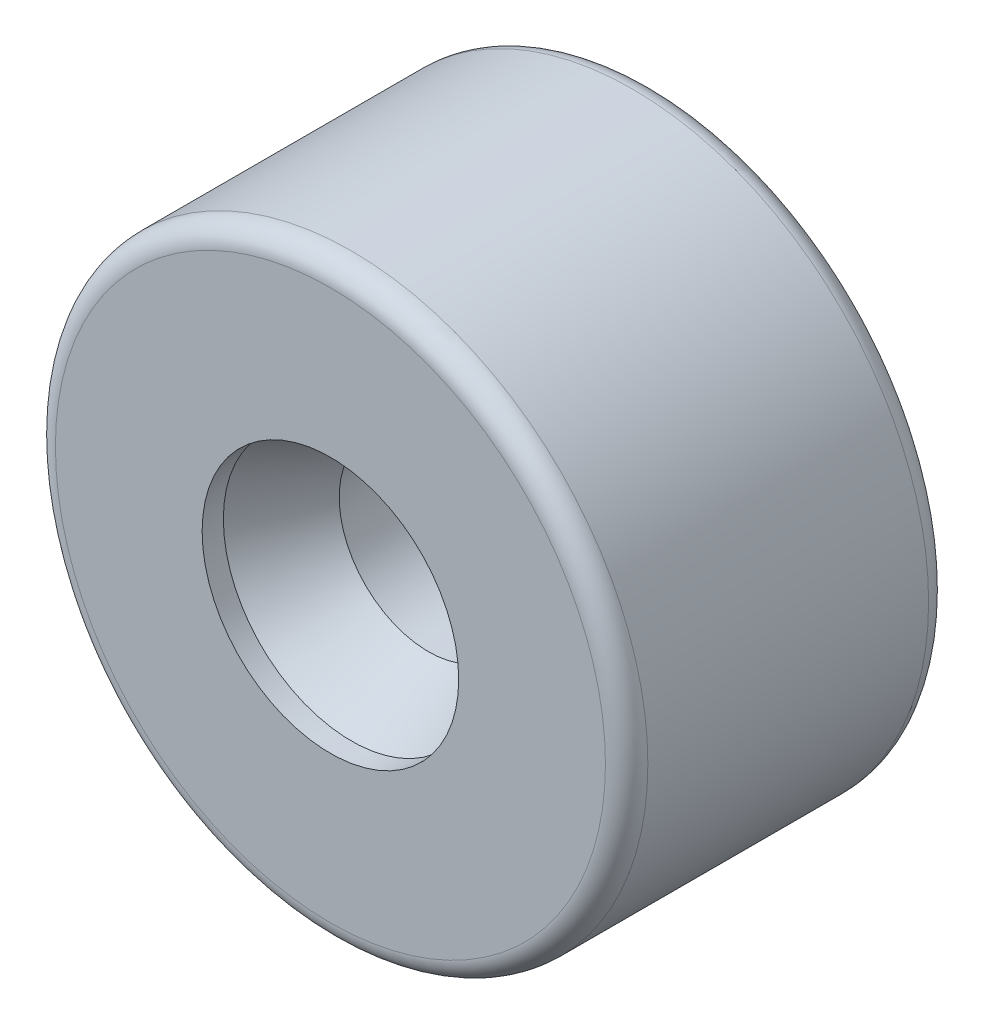
SolidWorks part; units mm, degrees
ref_plane "Front Plane" through (0, 0, 0) normal (0, 0, 1) x (1, 0, 0)
ref_plane "Top Plane" through (0, 0, 0) normal (0, 1, 0) x (1, 0, 0)
ref_plane "Right Plane" through (0, 0, 0) normal (1, 0, 0) x (0, 0, -1)
sketch "Sketch1" plane through (0, 0, 0) normal (1, 0, 0) x (0, 0, -1)
  line L0 (0, 10) -> (0, -10) construction
  line L1 (-361.4789, 0) -> (361.4789, 0) construction
  line L2 (30, 45.0552) -> (-30, 45.0552)
  line L3 (-30, 45.0552) -> (-66.2, 63.5)
  line L4 (-66.2, 63.5) -> (-76.2, 63.5)
  line L5 (-76.2, 63.5) -> (-76.2, 60.5)
  line L6 (-76.2, 60.5) -> (-66.2, 60.5)
  line L7 (-66.2, 60.5) -> (-30, 42.0552)
  line L8 (-30, 42.0552) -> (-1.5, 42.0552)
  line L9 (-1.5, 42.0552) -> (-1.5, 10)
  line L11 (-1.5, 10) -> (1.5, 10)
  line L12 (0, 10) -> (0, 78.3387) construction
  line L13 (1.5, 42.0552) -> (1.5, 10)
  line L14 (30, 42.0552) -> (1.5, 42.0552)
  line L15 (30, 45.0552) -> (66.2, 63.5)
  line L16 (66.2, 60.5) -> (30, 42.0552)
  line L17 (76.2, 60.5) -> (66.2, 60.5)
  line L18 (76.2, 63.5) -> (76.2, 60.5)
  line L19 (66.2, 63.5) -> (76.2, 63.5)
  point P4 (0, 0)
  point P8 (0, 0)
  point P23 (0, 45.0552)
  dimension "D1" = 153
  dimension "D2" = 30
  dimension "D3" = 10
  dimension "D4" = 76.2
  dimension "D5" = 3
  dimension "D6" = 63.5
  dimension "D7" = 1.5
  dimension "D8" = 3
  dimension "D9" = 10
revolve "Revolve1" add sketch "Sketch1" angle 360 about L1
sketch "Sketch2" plane through (0, 0, -1.5) normal (0, 0, -1) x (-1, 0, 0)
  circle A0 centre (0, 0) radius 30
  circle A1 centre (0, 30) radius 4
  circle A2 centre (30, 0) radius 4
  circle A3 centre (0, -30) radius 4
  circle A4 centre (-30, 0) radius 4
  dimension "D1" = 60
  dimension "D2" = 8
extrude "Cut-Extrude1" cut sketch "Sketch2" against normal blind 10 contours A0 A1 | A0 A1 | A0 A4 | A0 A4 | A0 A2 | A0 A2 | A0 A3 | A0 A3
sketch "Sketch3" plane through (0, 0, 0) normal (1, 0, 0) x (0, 0, -1)
  line L0 (0, 73.5893) -> (0, -73.5893) construction
  line L1 (-155.8032, 0) -> (155.8032, 0) construction
  line L2 (-66.2, 139.7) -> (66.2, 139.7)
  line L3 (-76.2, 63.5) -> (-66.2, 63.5)
  line L4 (-66.2, 63.5) -> (-30, 45.0552)
  line L5 (-30, 45.0552) -> (30, 45.0552)
  line L6 (30, 45.0552) -> (-30, 45.0552) construction
  line L7 (30, 45.0552) -> (66.2, 63.5)
  line L8 (66.2, 63.5) -> (76.2, 63.5)
  line L9 (76.2, 63.5) -> (76.2, 129.7)
  line L10 (-76.2, 63.5) -> (-76.2, 129.7)
  line L11 (-66.2, 129.7) -> (66.2, 129.7)
  line L12 (68.7, 127.2) -> (68.7, 71)
  line L14 (27.9468, 52.6842) -> (-28.4532, 52.6842)
  line L15 (-28.4532, 52.6842) -> (-64.4, 71)
  line L16 (-64.4, 71) -> (-68.7, 71)
  line L17 (-68.7, 71) -> (-68.7, 127.2)
  line L18 (68.7, 71) -> (63.8936, 71)
  line L19 (63.8936, 71) -> (27.9468, 52.6842)
  arc A0 (76.2, 129.7) -> (66.2, 139.7) centre (66.2, 129.7) ccw
  arc A1 (-76.2, 129.7) -> (-66.2, 139.7) centre (-66.2, 129.7) cw
  arc A2 (66.2, 129.7) -> (68.7, 127.2) centre (66.2, 127.2) cw
  arc A3 (-66.2, 129.7) -> (-68.7, 127.2) centre (-66.2, 127.2) ccw
  point P4 (0, 0)
  point P8 (0, 0)
  point P37 (68.7, 129.7)
  point P40 (-68.7, 129.7)
  dimension "D2" = 10
  dimension "D9" = 2.5
  dimension "D1" = 139.7
  dimension "D3" = 58.7
  dimension "D4" = 7.5
  dimension "D5" = 56.4
  dimension "D6" = 7.5
  dimension "D7" = 58.7
  dimension "D8" = 4.3
revolve "Revolve2" add sketch "Sketch3" angle 360 about L1
